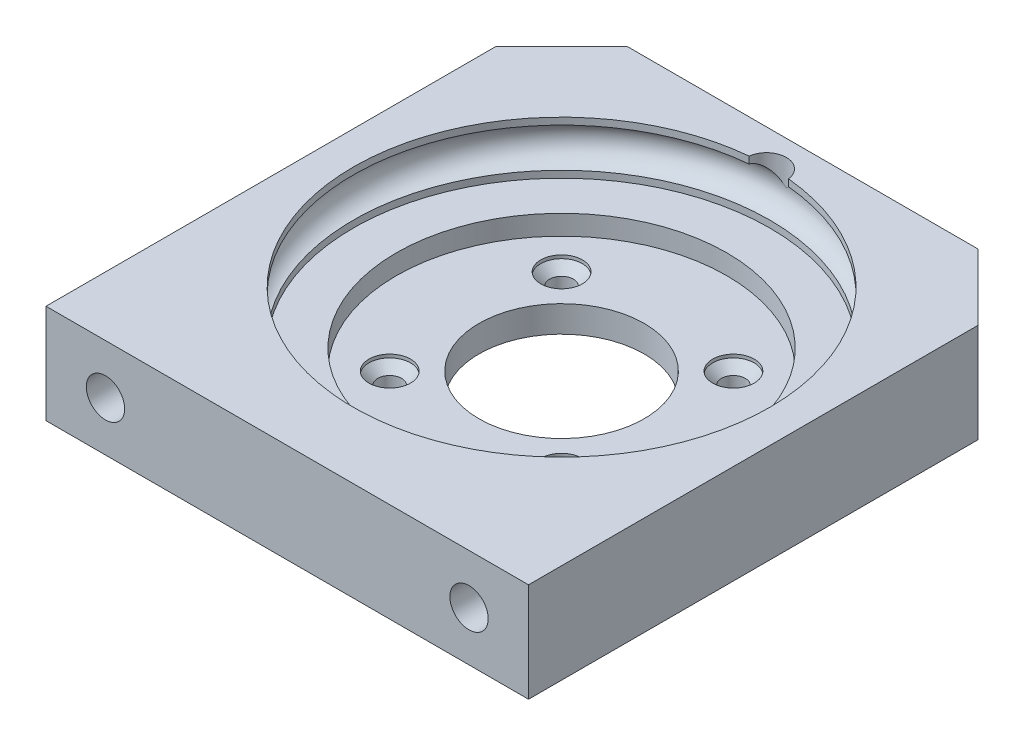
SolidWorks part; units mm, degrees
ref_plane "Front Plane" through (0, 0, 0) normal (0, 0, 1) x (1, 0, 0)
ref_plane "Top Plane" through (0, 0, 0) normal (0, 1, 0) x (1, 0, 0)
ref_plane "Right Plane" through (0, 0, 0) normal (1, 0, 0) x (0, 0, -1)
sketch "Sketch2" plane through (0, 0, 0) normal (0, 0, 1) x (1, 0, 0)
  line L0 (-25, 3) -> (-25, 0)
  line L1 (-25, 0) -> (-12.5, 0)
  line L2 (-12.5, 0) -> (-12.5, -4)
  line L3 (-12.5, -4) -> (-36.5, -4)
  line L4 (0, 0) -> (0, 12.8376) construction
  line L6 (-25, 3) -> (-31.5, 3)
  line L7 (-31.5, 3) -> (-31.5, 11)
  line L8 (-31.5, 11) -> (-36.5, 11)
  line L9 (-36.5, 11) -> (-36.5, -4)
  dimension "D1" = 25
  dimension "D2" = 50
  dimension "D3" = 63
  dimension "D4" = 5
  dimension "D5" = 4
  dimension "D6" = 3
  dimension "D7" = 8
revolve "Revolve1" add sketch "Sketch2" angle 360 about L4
sketch "Sketch3" plane through (0, 0, 0) normal (0, 1, 0) x (1, 0, 0)
  line L1 (-13, -13) -> (13, -13) construction
  line L2 (-13, -13) -> (-13, 13) construction
  line L3 (-13, 13) -> (13, 13) construction
  line L4 (13, -13) -> (13, 13) construction
  line L5 (-13, -13) -> (13, 13) construction
  line L6 (-13, 13) -> (13, -13) construction
  circle A0 centre (-13, 13) radius 1.25
  circle A1 centre (13, 13) radius 1.25
  circle A2 centre (13, -13) radius 1.25
  circle A3 centre (-13, -13) radius 1.25
  point P0 (0, 0)
  dimension "D2" = 2.5
  dimension "D1" = 26
extrude "Cut-Extrude1" cut sketch "Sketch3" against normal through all
sketch "Sketch4" plane through (0, 11, 0) normal (0, 1, 0) x (1, 0, 0)
  circle A0 centre (0, 0) radius 31.5
  circle A1 centre (0, 31.5) radius 1
  circle A2 centre (2.0939, 31.5212) radius 1
  circle A3 centre (4.1841, 31.3962) radius 1
  circle A4 centre (6.2605, 31.1258) radius 1
  circle A5 centre (8.313, 30.7112) radius 1
  circle A6 centre (10.3316, 30.1544) radius 1
  circle A7 centre (12.3065, 29.4582) radius 1
  circle A8 centre (14.2279, 28.6259) radius 1
  circle A9 centre (16.0866, 27.6616) radius 1
  circle A10 centre (17.8736, 26.5699) radius 1
  circle A11 centre (19.58, 25.3563) radius 1
  circle A12 centre (21.1976, 24.0267) radius 1
  circle A13 centre (22.7185, 22.5874) radius 1
  circle A14 centre (24.1353, 21.0455) radius 1
  circle A15 centre (25.4411, 19.4086) radius 1
  circle A16 centre (26.6295, 17.6845) radius 1
  circle A17 centre (27.6948, 15.8818) radius 1
  circle A18 centre (28.6317, 14.0091) radius 1
  circle A19 centre (29.4357, 12.0756) radius 1
  circle A20 centre (30.1029, 10.0908) radius 1
  circle A21 centre (30.63, 8.0643) radius 1
  circle A22 centre (31.0145, 6.0059) radius 1
  circle A23 centre (31.2544, 3.9257) radius 1
  circle A24 centre (31.3487, 1.8339) radius 1
  circle A25 centre (31.2968, -0.2595) radius 1
  circle A26 centre (31.099, -2.3441) radius 1
  circle A27 centre (30.7562, -4.4098) radius 1
  circle A28 centre (30.2702, -6.4466) radius 1
  circle A29 centre (29.6433, -8.4445) radius 1
  circle A30 centre (28.8786, -10.3939) radius 1
  circle A31 centre (27.9797, -12.2851) radius 1
  circle A32 centre (26.9511, -14.109) radius 1
  circle A33 centre (25.7978, -15.8568) radius 1
  circle A34 centre (24.5254, -17.5198) radius 1
  circle A35 centre (23.1401, -19.09) radius 1
  circle A36 centre (21.6486, -20.5598) radius 1
  circle A37 centre (20.0582, -21.9219) radius 1
  circle A38 centre (18.3767, -23.1698) radius 1
  circle A39 centre (16.6122, -24.2973) radius 1
  circle A40 centre (14.7734, -25.299) radius 1
  circle A41 centre (12.8692, -26.17) radius 1
  circle A42 centre (10.9088, -26.9061) radius 1
  circle A43 centre (8.9019, -27.5036) radius 1
  circle A44 centre (6.8582, -27.9596) radius 1
  circle A45 centre (4.7877, -28.272) radius 1
  circle A46 centre (2.7004, -28.4392) radius 1
  circle A47 centre (0.6065, -28.4604) radius 1
  circle A48 centre (-1.4837, -28.3355) radius 1
  circle A49 centre (-3.5601, -28.065) radius 1
  circle A50 centre (-5.6126, -27.6504) radius 1
  circle A51 centre (-7.6312, -27.0936) radius 1
  circle A52 centre (-9.6061, -26.3974) radius 1
  circle A53 centre (-11.5275, -25.5651) radius 1
  circle A54 centre (-13.3862, -24.6008) radius 1
  circle A55 centre (-15.1732, -23.5091) radius 1
  circle A56 centre (-16.8796, -22.2955) radius 1
  circle A57 centre (-18.4972, -20.9659) radius 1
  circle A58 centre (-20.0181, -19.5266) radius 1
  circle A59 centre (-21.4349, -17.9847) radius 1
  circle A60 centre (-22.7407, -16.3478) radius 1
  circle A61 centre (-23.9291, -14.6237) radius 1
  circle A62 centre (-24.9944, -12.821) radius 1
  circle A63 centre (-25.9313, -10.9483) radius 1
  circle A64 centre (-26.7354, -9.0148) radius 1
  circle A65 centre (-27.4025, -7.03) radius 1
  circle A66 centre (-27.9296, -5.0035) radius 1
  circle A67 centre (-28.3141, -2.9451) radius 1
  circle A68 centre (-28.554, -0.8649) radius 1
  circle A69 centre (-28.6483, 1.2269) radius 1
  circle A70 centre (-28.5964, 3.3203) radius 1
  circle A71 centre (-28.3986, 5.4049) radius 1
  circle A72 centre (-28.0558, 7.4706) radius 1
  circle A73 centre (-27.5698, 9.5074) radius 1
  circle A74 centre (-26.9429, 11.5053) radius 1
  circle A75 centre (-26.1782, 13.4547) radius 1
  circle A76 centre (-25.2793, 15.3459) radius 1
  circle A77 centre (-24.2507, 17.1698) radius 1
  circle A78 centre (-23.0974, 18.9176) radius 1
  circle A79 centre (-21.825, 20.5806) radius 1
  circle A80 centre (-20.4397, 22.1508) radius 1
  circle A81 centre (-18.9482, 23.6206) radius 1
  circle A82 centre (-17.3578, 24.9827) radius 1
  circle A83 centre (-15.6763, 26.2306) radius 1
  circle A84 centre (-13.9118, 27.3581) radius 1
  circle A85 centre (-12.073, 28.3598) radius 1
  circle A86 centre (-10.1688, 29.2308) radius 1
  circle A87 centre (-8.2084, 29.9669) radius 1
  circle A88 centre (-6.2015, 30.5644) radius 1
  circle A89 centre (-4.1578, 31.0204) radius 1
  circle A90 centre (-2.0873, 31.3328) radius 1
  circle A91 centre (0, 0) radius 31.5 construction
  dimension "D1" = 2
  dimension "D3" = 0.094
  dimension "D2" = 90
sketch "Sketch5" plane through (0, 0, 0) normal (0, 0, 1) x (1, 0, 0)
  line L0 (31.5, 7) -> (31, 7) construction
  line L1 (31.5, 3) -> (31.5, 11) construction
  line L2 (0, 0) -> (0, -3.9123) construction
  circle A0 centre (31, 7) radius 3
  dimension "D1" = 6
  dimension "D2" = 0.5
revolve "Cut-Revolve1" cut sketch "Sketch5" angle 360 about L2
ref_plane "Plane1" through (0, 7, 0) normal (0, 1, 0) x (1, 0, 0)
sketch "Sketch6" plane through (0, 7, 0) normal (0, 1, 0) x (1, 0, 0)
  circle A0 centre (0, 31) radius 3
  circle A1 centre (0, 0) radius 31.5 construction
  dimension "D1" = 6
  dimension "D2" = 0.5
extrude "Cut-Extrude2" cut sketch "Sketch6" along normal blind 10
sketch "Sketch7" plane through (0, 11, 0) normal (0, 1, 0) x (1, 0, 0)
  line L0 (-36.5, 0) -> (-36.5, -41.5)
  line L1 (-36.5, -41.5) -> (36.5, -41.5)
  line L2 (36.5, -41.5) -> (36.5, 0)
  circle A0 centre (0, 0) radius 36.5 construction
  arc A1 (-36.5, 0) -> (36.5, 0) centre (0, 0) ccw
  dimension "D1" = 5
extrude "Boss-Extrude1" add sketch "Sketch7" against normal up to surface (15 mm away) up to face at (-13, -4, 14.25)
sketch "Sketch9" plane through (0, 0, 41.5) normal (0, 0, 1) x (1, 0, 0)
  line L0 (-36.5, 3.5) -> (-27.5, 3.5) construction
  line L1 (-36.5, -4) -> (-36.5, 11) construction
  line L2 (0, -8.984) -> (0, 0) construction
  circle A0 centre (-27.5, 3.5) radius 2.9
  circle A1 centre (27.5, 3.5) radius 2.9
  dimension "D1" = 55
  dimension "D2" = 5.8
extrude "Cut-Extrude3" cut sketch "Sketch9" against normal blind 6.5
hole_wizard "CSK for M3 Countersunk Flat Head Screw1" positions "Sketch10" profile "Sketch11" countersink size "M3" standard "ISO" end condition through all
sketch "Sketch10" plane through (0, 0, 0) normal (0, 1, 0) x (1, 0, 0)
  point P0 (13, 13)
  point P3 (13, -13)
  point P6 (-13, -13)
  point P9 (-13, 13)
sketch "Sketch11" plane through (13, 0, -13) normal (1, 0, 0) x (0, 0, 1)
  line L0 (0, 0) -> (0, 4)
  line L1 (0, 4) -> (1.8, 4)
  line L2 (1.8, 4) -> (1.8, 1.85)
  line L3 (1.8, 1.85) -> (3.15, 0.5)
  line L4 (3.15, 0.5) -> (3.15, 0)
  line L6 (3.15, 0) -> (0, 0)
  line L7 (-1.8, 1.85) -> (-3.15, 0.5) construction
  line L11 (0, -6.35) -> (0, 107.95) construction
  dimension "Thru Hole Dia." = 3.6
  dimension "Thru Hole Depth" = 4
  dimension "C'Sink Dia." = 6.3
  dimension "C'Sink Angle" = 90
  dimension "Head Clearance" = 0.5
sketch "Sketch12" plane through (0, 11, 0) normal (0, 1, 0) x (1, 0, 0)
  line L0 (-36.5, 0) -> (-36.5, 26.5)
  line L1 (-36.5, 26.5) -> (-26.5, 36.5)
  line L2 (-26.5, 36.5) -> (26.5, 36.5)
  line L3 (0, 0) -> (0, -5.9791) construction
  line L4 (36.5, 26.5) -> (26.5, 36.5)
  line L5 (36.5, 0) -> (36.5, 26.5)
  arc A0 (36.5, 0) -> (-36.5, 0) centre (0, 0) ccw construction
  arc A1 (36.5, 0) -> (-36.5, 0) centre (0, 0) ccw
  point P12 (0, 36.5)
  arc M3 (36.5, 0) -> (-36.5, 0) centre (0, 0) ccw
  dimension "D1" = 10
  dimension "D2" = 45
extrude "Boss-Extrude2" add sketch "Sketch12" against normal up to surface (15 mm away) contours L2 L1 L0 M3 | L5 L4 L2 M3
